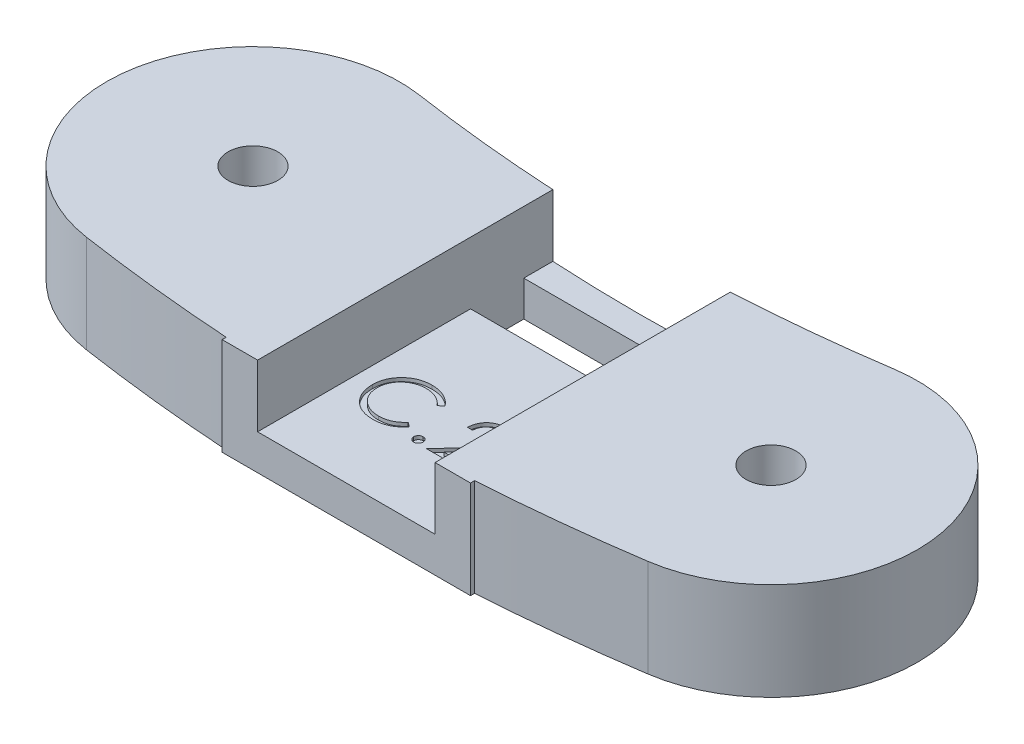
SolidWorks part; units mm, degrees
material "ABS"
ref_plane "Front Plane" through (0, 0, 0) normal (0, 0, 1) x (1, 0, 0)
ref_plane "Top Plane" through (0, 0, 0) normal (0, 1, 0) x (1, 0, 0)
ref_plane "Right Plane" through (0, 0, 0) normal (1, 0, 0) x (0, 0, -1)
sketch "Sketch2" plane through (0, 0, 0) normal (0, 1, 0) x (1, 0, 0)
  line L0 (0, 105) -> (0, 0) construction
  line L1 (13.3768, 15.4941) -> (15.8156, -0.8247) construction
  line L3 (13.3768, 15.4941) -> (0, 105) construction
  line L6 (0, 105) -> (-14.5962, 7.3347) construction
  arc A0 (-13.3768, 15.4941) -> (13.3768, 15.4941) centre (0, 105) ccw
  arc A1 (-15.8156, -0.8247) -> (15.8156, -0.8247) centre (0, 105) ccw
  arc A2 (-33.4311, 12.0811) -> (33.4311, 12.0811) centre (0, 105) ccw construction
  arc A3 (-13.3768, 15.4941) -> (-15.8156, -0.8247) centre (-14.5962, 7.3347) ccw
  arc A4 (15.8156, -0.8247) -> (13.3768, 15.4941) centre (14.5962, 7.3347) ccw
  circle A6 centre (0, 105) radius 90.5 construction
  circle A7 centre (0, 105) radius 92.5 construction
  arc A8 (-18.8033, 14.4313) -> (18.8033, 14.4313) centre (0, 105) ccw construction
  arc A9 (-20.9883, 2.1191) -> (20.9883, 2.1191) centre (0, 105) ccw construction
  circle A10 centre (0, 105) radius 105 construction
  circle A11 centre (0, 105) radius 107 construction
  circle A12 centre (-14.5962, 7.3347) radius 1.4
  circle A13 centre (14.5962, 7.3347) radius 1.4
  point P4 (88.4582, 132.0444)
  point P9 (100.412, 135.699)
  point P17 (90.5, 105)
  point P22 (107, 105)
  dimension "D3" = 185
  dimension "D4" = 210
  dimension "D7" = 197.5
  dimension "D5" = 2
  dimension "D6" = 2
extrude "Boss-Extrude1" add sketch "Sketch2" along normal blind 14
ref_plane "Plane1" through (0, 0, 2) normal (0, 0, 1) x (1, 0, 0)
sketch "Sketch3" plane through (0, 0, 2) normal (0, 0, 1) x (1, 0, 0)
  line L0 (0, 0) -> (0, 14) construction
  line L2 (-7, 14) -> (7, 14)
  line L4 (7, 14) -> (7, 0)
  line L5 (7, 0) -> (-7, 0)
  line L6 (-7, 0) -> (-7, 14)
  line L7 (15.8156, 14) -> (-15.8156, 14) construction
  line L8 (-15.8156, 0) -> (15.8156, 0) construction
  circle A0 centre (0, 7) radius 7 construction
  circle A1 centre (0, 7) radius 3 construction
extrude "Boss-Extrude2" add sketch "Sketch3" against normal up to body separate body contours L2 L4 L5 L6
sketch "Sketch19" plane through (0, 0, 2) normal (0, 0, 1) x (1, 0, 0)
  line L0 (-7, 7) -> (-33.8084, 7) construction
  line L1 (-13.3768, 14) -> (-22.8462, 14) construction
  line L3 (-13.3768, 14) -> (-22.8462, 14)
  line L4 (-7, 0) -> (-7, 14)
  line L5 (-7, 14) -> (-15.8156, 14) construction
  line L7 (-22.8462, 0) -> (-7, 0)
  line L8 (-7, 8.5) -> (-22.8462, 8.5)
  line L9 (-7, 5.5) -> (-22.8462, 5.5)
  line L10 (-7, 0) -> (-7, 14) construction
  line L11 (-7, 14) -> (-15.8156, 14)
  line L12 (-22.8462, 14) -> (-22.8462, 0)
  line L14 (-7, 8.5) -> (-33.8084, 8.5) construction
  line L15 (-7, 5.5) -> (-33.8084, 5.5) construction
  dimension "D1" = 1.5
  dimension "D2" = 1.5
extrude "Cut-Extrude4" cut sketch "Sketch19" against normal blind 22 contours L8 L12 L9 L4
ref_plane "Plane10" through (0, 0, -15.4941) normal (0, 0, 1) x (1, 0, 0)
mirror "Mirror2" about plane through (0, 0, 0) normal (1, 0, 0) of "Cut-Extrude4"
sketch "Sketch24" plane through (0, 0, 2) normal (0, 0, 1) x (1, 0, 0)
  line L0 (-7, 8.5) -> (-5, 8.5)
  line L1 (7, 5.5) -> (5, 5.5)
  line L2 (5, 12) -> (-5, 12)
  line L3 (-5, 12) -> (-5, 8.5)
  line L4 (-7, 14) -> (-7, 0)
  line L5 (-7, 0) -> (7, 0)
  line L6 (7, 0) -> (7, 14)
  line L7 (7, 14) -> (-7, 14)
  line L8 (-7, 14) -> (-7, 0)
  line L9 (-7, 0) -> (7, 0)
  line L10 (7, 0) -> (7, 14)
  line L11 (7, 14) -> (-7, 14)
  line L12 (-5, 2) -> (5, 2)
  line L13 (5, 2) -> (5, 5.5)
  line L14 (-5, 5.5) -> (-5, 2)
  line L15 (5, 8.5) -> (7, 8.5)
  line L16 (-5, 12) -> (-5, 2) construction
  line L17 (-5, 5.5) -> (-7, 5.5)
  line L18 (5, 8.5) -> (5, 12)
  line L20 (5, 2) -> (5, 12) construction
  line M5 (-7, 14) -> (-7, 0)
  line M7 (7, 0) -> (7, 14)
  dimension "D1" = 0
  dimension "D2" = 2
extrude "Cut-Extrude8" cut sketch "Sketch24" against normal through all contours L15 L18 L2 L3 L0 L17 L14 L12 L13 L1 M5 M7
sketch "Sketch25" plane through (0, 2, 0) normal (0, 1, 0) x (1, 0, 0)
  line L0 (-7, -2) -> (7, -2) construction
  line L1 (-5, 13) -> (5, 13)
  line L2 (-5, 10) -> (5, 10)
  line L3 (-5, 14.6382) -> (-5, -2) construction
  line L4 (5, 14.6382) -> (5, -2) construction
  line L5 (-5, 13) -> (-5, 10)
  line L6 (5, 13) -> (5, 10)
  line L8 (-7, 10) -> (7, 10) construction
  line L9 (-7, 13) -> (7, 13) construction
  dimension "D1" = 15
  dimension "D2" = 3
extrude "Cut-Extrude9" cut sketch "Sketch25" against normal blind 2
sketch "Sketch26" plane through (0, 2, 0) normal (0, 1, 0) x (1, 0, 0)
  text T0 "C.2\r\n"
extrude "Cut-Extrude10" cut sketch "Sketch26" against normal blind 0.2
